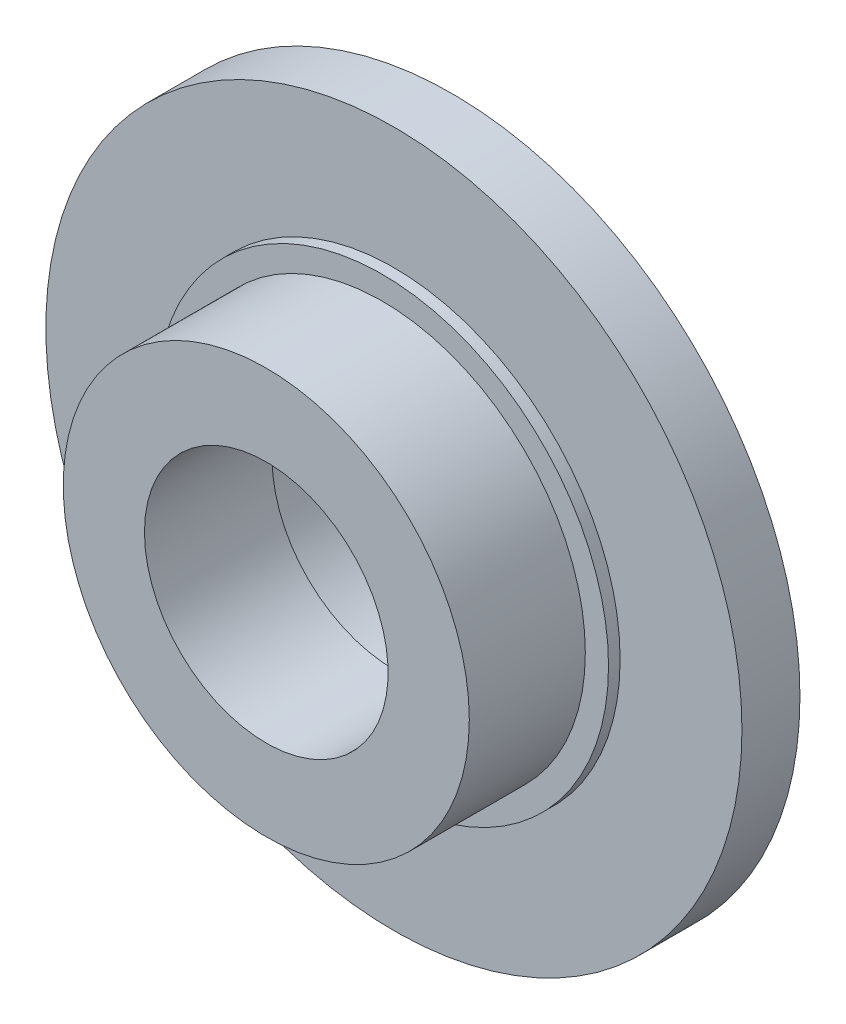
SolidWorks part; units mm, degrees
ref_plane "Front Plane" through (0, 0, 0) normal (0, 0, 1) x (1, 0, 0)
ref_plane "Top Plane" through (0, 0, 0) normal (0, 1, 0) x (1, 0, 0)
ref_plane "Right Plane" through (0, 0, 0) normal (1, 0, 0) x (0, 0, -1)
sketch "Sketch1" plane through (0, 0, 0) normal (0, 0, 1) x (1, 0, 0)
  circle A0 centre (0, 0) radius 30
  dimension "D1" = 60
extrude "Boss-Extrude1" add sketch "Sketch1" along normal blind 5
sketch "Sketch2" plane through (0, 0, 5) normal (0, 0, 1) x (1, 0, 0)
  circle A0 centre (0, 0) radius 19.5
  dimension "D1" = 39
extrude "Boss-Extrude2" add sketch "Sketch2" along normal blind 1
sketch "Sketch3" plane through (0, 0, 6) normal (0, 0, 1) x (1, 0, 0)
  circle A0 centre (0, 0) radius 17.5
  dimension "D1" = 35
extrude "Boss-Extrude3" add sketch "Sketch3" along normal blind 10
sketch "Sketch5" plane through (0, 0, 5) normal (0, 0, 1) x (1, 0, 0)
  line L0 (0, 0) -> (44.5119, 0) construction
  circle A0 centre (0, 0) radius 24.5 construction
  circle A2 centre (24.5, 0) radius 2.05
  circle A3 centre (12.25, -21.2176) radius 2.05
  circle A4 centre (-12.25, -21.2176) radius 2.05
  circle A5 centre (-24.5, 0) radius 2.05
  circle A6 centre (-12.25, 21.2176) radius 2.05
  circle A7 centre (12.25, 21.2176) radius 2.05
  point P19 (0, 0)
  dimension "D1" = 49
  dimension "D2" = 4.1
  dimension "D3" = 6
extrude "Cut-Extrude1" cut sketch "Sketch5" against normal blind 4 and the other way blind 4 from surface at -5 starting at face at (30, 0, 0)
sketch "Sketch9" plane through (0, 0, 0) normal (0, 0, -1) x (-1, 0, 0)
  circle A0 centre (0, 0) radius 5.5
  dimension "D1" = 11
extrude "Cut-Extrude5" cut sketch "Sketch9" against normal blind 4
sketch "Sketch7" plane through (0, 0, 0) normal (0, 0, -1) x (-1, 0, 0)
  circle A0 centre (0, 0) radius 12.025
  dimension "D1" = 24.05
extrude "Cut-Extrude3" cut sketch "Sketch7" against normal blind 5
sketch "Sketch8" plane through (0, 0, 5) normal (0, 0, -1) x (-1, 0, 0)
  circle A0 centre (0, 0) radius 10.5
  dimension "D1" = 21
extrude "Cut-Extrude4" cut sketch "Sketch8" against normal through all
